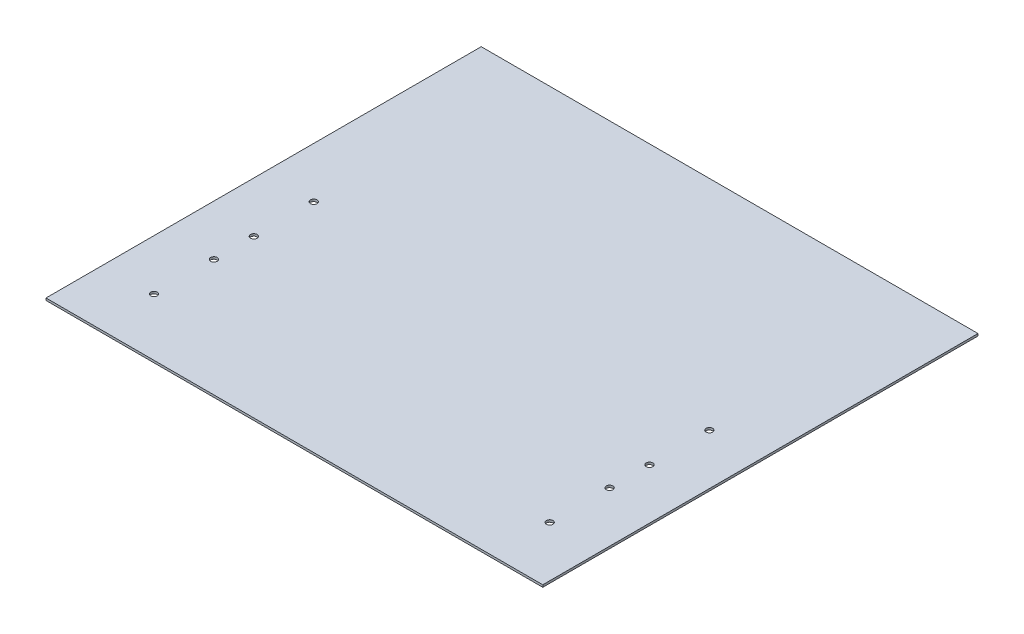
SolidWorks part; units mm, degrees
ref_plane "Front Plane" through (0, 0, 0) normal (0, 0, 1) x (1, 0, 0)
ref_plane "Top Plane" through (0, 0, 0) normal (0, 1, 0) x (1, 0, 0)
ref_plane "Right Plane" through (0, 0, 0) normal (1, 0, 0) x (0, 0, -1)
sketch "Sketch1" plane through (0, 0, 0) normal (0, 1, 0) x (1, 0, 0)
  line L1 (0, 0) -> (226, 0)
  line L2 (0, 0) -> (0, 198)
  line L3 (0, 198) -> (226, 198)
  line L4 (226, 0) -> (226, 198)
  dimension "D1" = 226
  dimension "D2" = 198
extrude "Boss-Extrude1" add sketch "Sketch1" along normal blind 1
sketch "Input for speaker" plane through (0, 1, 0) normal (0, 1, 0) x (1, 0, 0)
  line L0 (28, 198) -> (28, 0) construction
  line L1 (226, 198) -> (0, 198) construction
  line L2 (42, 10) -> (184, 10) construction
  line L3 (184, 10) -> (184, 0) construction
  line L4 (32, 10) -> (42, 10) construction
  line L5 (32, 10) -> (32, 0) construction
  line L6 (42, 10) -> (42, 0) construction
  line L7 (113, 198) -> (113, 0) construction
  line L8 (113, 97.5) -> (0, 97.5) construction
  line L9 (113, 97.5) -> (226, 97.5) construction
  line L10 (0, 0) -> (226, 0) construction
  line L11 (0, 198) -> (0, 0) construction
  line L12 (198, 198) -> (198, 0) construction
  line L13 (226, 0) -> (226, 198) construction
  line L14 (194, 10) -> (194, 0) construction
  line L15 (194, 10) -> (184, 10) construction
  point P1 (32, 5)
  point P23 (194, 5)
  point P26 (113, 10)
  dimension "D1" = 42
  dimension "D2" = 28
  dimension "D3" = 10
  dimension "D4" = 10
  dimension "D5" = 97.5
sketch "Sketch2" plane through (0, 1, 0) normal (0, 1, 0) x (1, 0, 0)
  line L0 (226, 0) -> (226, 198) construction
  line L1 (0, 0) -> (226, 0) construction
  line L2 (203, 98.7978) -> (203, 26.16) construction
  line L3 (113, 198) -> (113, 0) construction
  circle A4 centre (203, 26.16) radius 1.5
  circle A5 centre (203, 53.4) radius 1.5
  circle A6 centre (203, 71.5578) radius 1.5
  circle A7 centre (203, 98.7978) radius 1.5
  circle A8 centre (23, 26.16) radius 1.5
  circle A9 centre (23, 53.4) radius 1.5
  circle A10 centre (23, 71.5578) radius 1.5
  circle A11 centre (23, 98.7978) radius 1.5
  dimension "D5" = 26.16
  dimension "D6" = 27.24
  dimension "D7" = 18.1578
  dimension "D8" = 27.24
  dimension "D10" = 3
  dimension "D11" = 3
  dimension "D12" = 3
  dimension "D13" = 3
  dimension "D9" = 23
extrude "Cut-Extrude1" cut sketch "Sketch2" against normal blind 1
